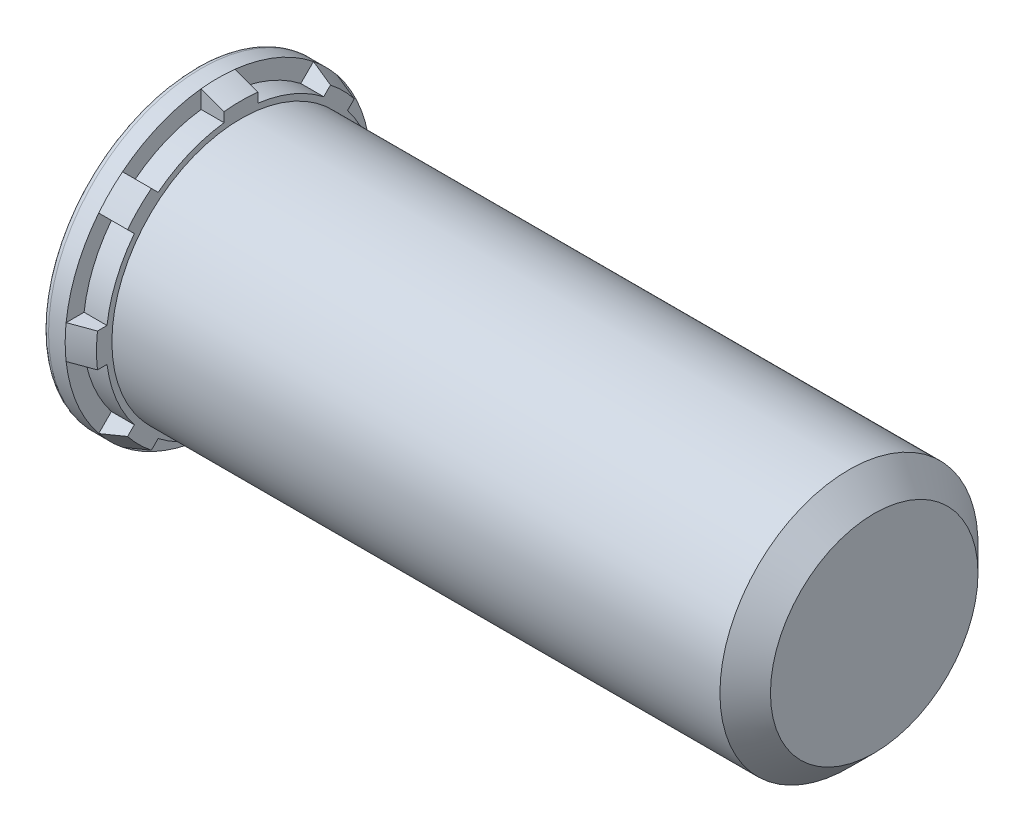
SolidWorks part; units mm, degrees
revolve "BaseBody" add sketch "BodySke" angle 360 about L6
sketch "BodySke" plane through (0, 0, 0) normal (0, 0, 1) x (1, 0, 0)
  line L0 (-0.4286, 2.7407) -> (-0.4286, 0)
  line L1 (0.4286, 2.7015) -> (0.4286, 2.413)
  line L2 (0, 2.8575) -> (0.4286, 2.7015)
  line L3 (0.4286, 2.413) -> (11.7989, 2.413)
  line L4 (12.2714, 1.9406) -> (12.2714, 0)
  line L5 (12.2714, 0) -> (-0.4286, 0)
  line L6 (0, 0) -> (50.554, 0) construction
  line L7 (-0.4286, 2.7407) -> (-0.4261, 2.7407)
  line L8 (12.2714, 1.9406) -> (11.7989, 2.413)
  line L9 (-0.3118, 2.8575) -> (0, 2.8575)
  line L11 (0.7925, 19.05) -> (0.7925, -3.175) construction
  line L13 (-0.4261, 2.7407) -> (-0.4261, 2.7432)
  arc A0 (-0.4261, 2.7432) -> (-0.3118, 2.8575) centre (-0.3118, 2.7432) cw
  dimension "Fillet_rad" = 0.1143
  dimension "Body_ch_ang" = 45
  dimension "Minor_dia" = 3.8811
  dimension "Diameter" = 4.826
  dimension "H_dia" = 5.715
  dimension "Advance" = 0.7925
  dimension "D1" = 20
  dimension "Length" = 12.7
  dimension "D2" = 0.0025
  dimension "D3" = 0.0025
  dimension "Clinch_ht" = 0.4286
  dimension "Head_ht" = 0.8572
cosmetic thread "ThreadCosmetic" [suppressed] parameters "Thread_length"=10.16, "Thread_minor"=3.8811
ref_plane "Plane1" through (0, 0, 0) normal (0, 0, 1) x (1, 0, 0)
ref_plane "Plane2" through (0, 0, 0) normal (0, 1, 0) x (1, 0, 0)
ref_plane "Plane3" through (0, 0, 0) normal (1, 0, 0) x (0, 0, -1)
sketch "ThdSchSke" plane through (0, 0, 0) normal (0, 0, 1) x (1, 0, 0)
  line L0 (2.1114, -1.9406) -> (1.7806, -2.413)
  line L1 (2.1114, -1.9406) -> (2.4422, -2.413)
  line L2 (2.4422, -2.413) -> (2.4422, -3.0162)
  line L3 (-3.175, 0) -> (5.1513, 0) construction
  line L5 (2.4422, -3.0162) -> (1.7806, -3.0162)
  line L6 (1.7806, -3.0162) -> (1.7806, -2.413)
  line L7 (-0.4286, 2.7407) -> (-0.4286, -2.7407) construction
  dimension "Diameter" = 4.826
  dimension "Thread_minor" = 3.8811
  dimension "Start" = 2.54
revolve "ThreadSchematic" [suppressed] cut sketch "ThdSchSke" angle 360 about L3
pattern_linear "ThdSchPat" [suppressed]
sketch "RibCutSke" plane through (0.4286, 1.7944, -0.091) normal (1, 0, 0) x (0, 0, -1)
  line L0 (0.224, 0.71) -> (0.224, 1.0457)
  line L1 (1.4572, 0.1992) -> (1.6946, 0.4366)
  line L2 (0.224, 0.598) -> (0.224, 0.0891) construction
  line L3 (-0.091, -1.7944) -> (-0.091, 5.0239) construction
  line L4 (-0.091, -1.7944) -> (0.224, 0.598) construction
  line L5 (-0.091, -1.7944) -> (1.378, 0.12) construction
  line L6 (1.378, 0.12) -> (1.0232, -0.2348) construction
  arc A1 (1.4572, 0.1992) -> (0.224, 0.71) centre (-0.091, -1.7944) ccw
  arc A2 (1.6946, 0.4366) -> (0.224, 1.0457) centre (-0.091, -1.7944) ccw
  circle A3 centre (-0.091, -1.7944) radius 2.7015 construction
  circle A4 centre (-0.091, -1.7944) radius 2.413 construction
  dimension "Rib_root_half_angle" = 7.5
  dimension "Rib_root_gap_angle" = 30
  dimension "Angle" = 45
extrude "RibCut" cut sketch "RibCutSke" against normal blind 0.4286
pattern_circular "RibCutsPat" count 8 every 45 about axis through (0, 0, 0) along (1, 0, 0) of "RibCut"
equation "' \"Length@BodySke\" = 0.5"
equation "' \"H_dia@BodySke\" = 0.225"
equation "' \"Start@ThdSchSke\" = 0.1"
equation "' \"Diameter@BodySke\" = 0.19"
equation "' \"Minor_dia@BodySke\" = 0.1528"
equation "' \"Advance@BodySke\" = 0.0312"
equation "\"Fillet_rad@BodySke\" =   \"H_dia@BodySke\" *0.02"
equation "\"Clinch_ht@BodySke\" = \"H_dia@BodySke\" * 0.075"
equation "\"Head_ht@BodySke\" =  \"H_dia@BodySke\" * 0.15"
equation "\"Num_ribs@RibCutsPat\" = 8"
equation "\"Angle@RibCutSke\" =\"Angle@RibCutsPat\""
equation "\"Rib_root_half_angle@RibCutSke\" = \"Angle@RibCutSke\" / 6"
equation "\"Rib_root_gap_angle@RibCutSke\" = \"Angle@RibCutSke\" - (2 * \"Rib_root_half_angle@RibCutSke\" )"
equation "\"Rib_root_dia@RibCutSke\" = \"Diameter@BodySke\""
equation "\"Inner_dia@RibCutSke\" = \"Diameter@BodySke\" + ( \"H_dia@BodySke\" - \"Diameter@BodySke\" ) / 4"
equation "\"Outer_dia@RibCutSke\" = \"H_dia@BodySke\""
equation "\"Depth@RibCut\" = \"Clinch_ht@BodySke\""
equation "\"Thread_length@ThreadCosmetic\" = \"Length@BodySke\" - \"Start@ThdSchSke\""
equation "\"Thread_minor@ThreadCosmetic\" = \"Minor_dia@BodySke\""
equation "\"Thread_minor@ThdSchSke\" = \"Minor_dia@BodySke\""
equation "\"Diameter@ThdSchSke\" = \"Diameter@BodySke\""
equation "\"Overcut@ThdSchSke\" = \"Diameter@BodySke\" * 1.25"
equation "\"Num_threads@ThdSchPat\" = int( \"Thread_length@ThreadCosmetic\" / \"Advance@BodySke\" + 0.999 )  + 1"
equation "\"Advance@ThdSchPat\" = \"Thread_length@ThreadCosmetic\" /  (\"Num_threads@ThdSchPat\" - 1) 'relax it"
equation "\"Num_threads@ThdSchPat\" = \"Num_threads@ThdSchPat\" - sgn( \"Num_threads@ThdSchPat\" - 1) '---chamfered tips only---"
